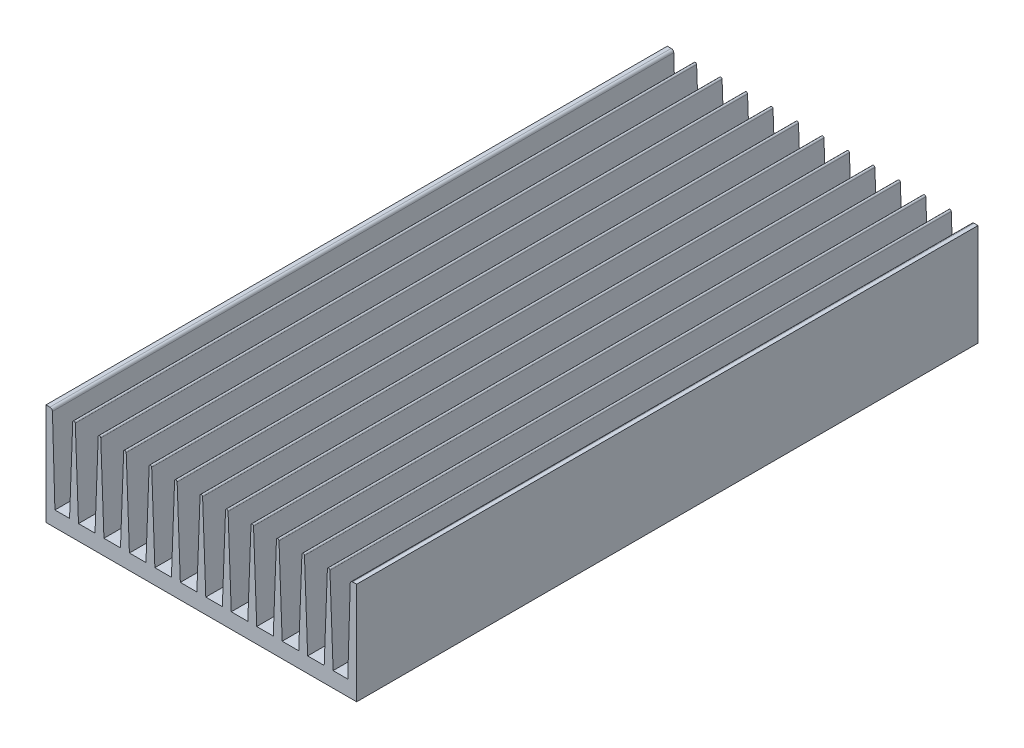
SolidWorks part; units mm, degrees
ref_plane "Спереди" through (0, 0, 0) normal (0, 0, 1) x (1, 0, 0)
ref_plane "Сверху" through (0, 0, 0) normal (0, 1, 0) x (1, 0, 0)
ref_plane "Справа" through (0, 0, 0) normal (1, 0, 0) x (0, 0, -1)
sketch "Эскиз1" plane through (0, 0, 0) normal (0, 0, 1) x (1, 0, 0)
  line L0 (0, 40) -> (1.529, 40)
  line L1 (0, 0) -> (122, 0)
  line L2 (2.5285, 39.0294) -> (3.5, 6)
  line L3 (0, 40) -> (0, 0)
  line L4 (122, 40) -> (122, 0)
  line L5 (61, 63.7127) -> (61, -22.2582) construction
  line L8 (122, 40) -> (120.471, 40)
  line L9 (119.4715, 39.0294) -> (118.5, 6)
  line L10 (3.5, 6) -> (118.5, 6)
  arc A0 (1.529, 40) -> (2.5285, 39.0294) centre (1.529, 39) cw
  arc A2 (120.471, 40) -> (119.4715, 39.0294) centre (120.471, 39) ccw
  point P18 (119.5, 40)
  dimension "D9" = 1
  dimension "D1" = 122
  dimension "D2" = 6
  dimension "D3" = 40
  dimension "D4" = 3.5
  dimension "D7" = 2.5
extrude "Вытянуть1" add sketch "Эскиз1" along normal blind 244
sketch "Эскиз2" plane through (0, 0, 244) normal (0, 0, 1) x (1, 0, 0)
  line L0 (118.5, 6) -> (3.5, 6) construction
  line L1 (10.5, 39.5) -> (9.25, 6)
  line L2 (11, 39.5) -> (11, 22.5548) construction
  line L3 (11.5, 39.5) -> (12.75, 6)
  line L4 (9.25, 6) -> (12.75, 6)
  line L6 (0, 40) -> (0, 0) construction
  arc A0 (10.5, 39.5) -> (11.5, 39.5) centre (11, 39.5) cw
  dimension "D1" = 34
  dimension "D3" = 0.5
  dimension "D2" = 3.5
  dimension "D4" = 11
  dimension "D5" = 1
extrude "Вытянуть3" add sketch "Эскиз2" against normal blind 244
pattern_curve "Кривая1" of "Вытянуть3" along edge at (61, 0, 0) parameters "D1"=11, "D3"=10, "D2"=1, "D4"=50
sketch "Эскиз3" plane through (0, 0, 0) normal (0, -1, 0) x (1, 0, 0)
  line L0 (-14.0506, 236) -> (137.5079, 236) construction
  line L1 (0, 244) -> (122, 244) construction
  line L2 (0, 244) -> (0, 0) construction
  line L3 (-46.7511, 122) -> (151.4312, 122) construction
  line L4 (0, 0) -> (122, 0) construction
  circle A0 centre (26, 236) radius 2.25
  circle A1 centre (96, 236) radius 2.25
  circle A2 centre (96, 8) radius 2.25
  circle A3 centre (26, 8) radius 2.25
  dimension "D2" = 70
  dimension "D4" = 4.5
  dimension "D1" = 8
  dimension "D3" = 26
extrude "Вырез-Вытянуть1" cut sketch "Эскиз3" against normal blind 6
sketch "Эскиз4" plane through (-5.7236, 0, -26.359) normal (0, -1, 0) x (1, 0, 0)
  line L0 (67.7236, 187.359) -> (67.7236, 64.1478) construction
  line L1 (107.9736, 183.759) -> (107.9736, 194.6849) construction
  line L3 (5.7236, 270.359) -> (127.7236, 270.359) construction
  line L4 (5.7236, 270.359) -> (5.7236, 26.359) construction
  circle A0 centre (94.2236, 89.359) radius 2.6
  circle A1 centre (67.7236, 187.359) radius 1.6
  circle A2 centre (67.7236, 52.359) radius 1.6
  circle A3 centre (107.9736, 183.759) radius 1.6
  circle A4 centre (107.9736, 99.959) radius 1.6
  dimension "D2" = 5.2
  dimension "D6" = 83.8
  dimension "D7" = 10.6
  dimension "D9" = 83
  dimension "D4" = 98
  dimension "D1" = 135
  dimension "D3" = 26.5
  dimension "D5" = 40.25
  dimension "D8" = 62
extrude "Вырез-Вытянуть2" cut sketch "Эскиз4" against normal blind 6
cosmetic thread "Условное изображение резьбы11" parameters "D2"=4
cosmetic thread "Условное изображение резьбы12" parameters "D2"=4
cosmetic thread "Условное изображение резьбы13" parameters "D2"=4
cosmetic thread "Условное изображение резьбы14" parameters "D2"=4
sketch "Эскиз5" plane through (128.3242, 0, 423.7759) normal (0, -1, 0) x (-1, 0, 0)
  line L0 (56.3242, 222.2759) -> (24.2196, 222.2759) construction
  line L1 (51.3242, 197.71) -> (51.3242, 229.3314) construction
  line L2 (6.3242, 179.7759) -> (6.3242, 423.7759) construction
  line L3 (128.3242, 179.7759) -> (6.3242, 179.7759) construction
  line L6 (128.3242, 179.7759) -> (128.3242, 423.7759) construction
  circle A0 centre (89.3242, 279.7759) radius 2.1
  circle A1 centre (21.3242, 239.7759) radius 1.6
  circle A2 centre (81.3242, 239.7759) radius 1.6
  circle A4 centre (81.3242, 204.7759) radius 1.6
  circle A5 centre (21.3242, 204.7759) radius 1.6
  dimension "D1" = 4.2
  dimension "D3" = 45
  dimension "D4" = 42.5
  dimension "D6" = 100
  dimension "D8" = 60
  dimension "D7" = 39
  dimension "D2" = 3.2
  dimension "D9" = 17.5
extrude "Вырез-Вытянуть3" cut sketch "Эскиз5" against normal blind 6
cosmetic thread "Условное изображение резьбы7" parameters "D2"=5
cosmetic thread "Условное изображение резьбы10" parameters "D2"=5
cosmetic thread "Условное изображение резьбы15" parameters "D2"=4
cosmetic thread "Условное изображение резьбы16" parameters "D2"=4
cosmetic thread "Условное изображение резьбы17" parameters "D2"=4
cosmetic thread "Условное изображение резьбы18" parameters "D2"=4
